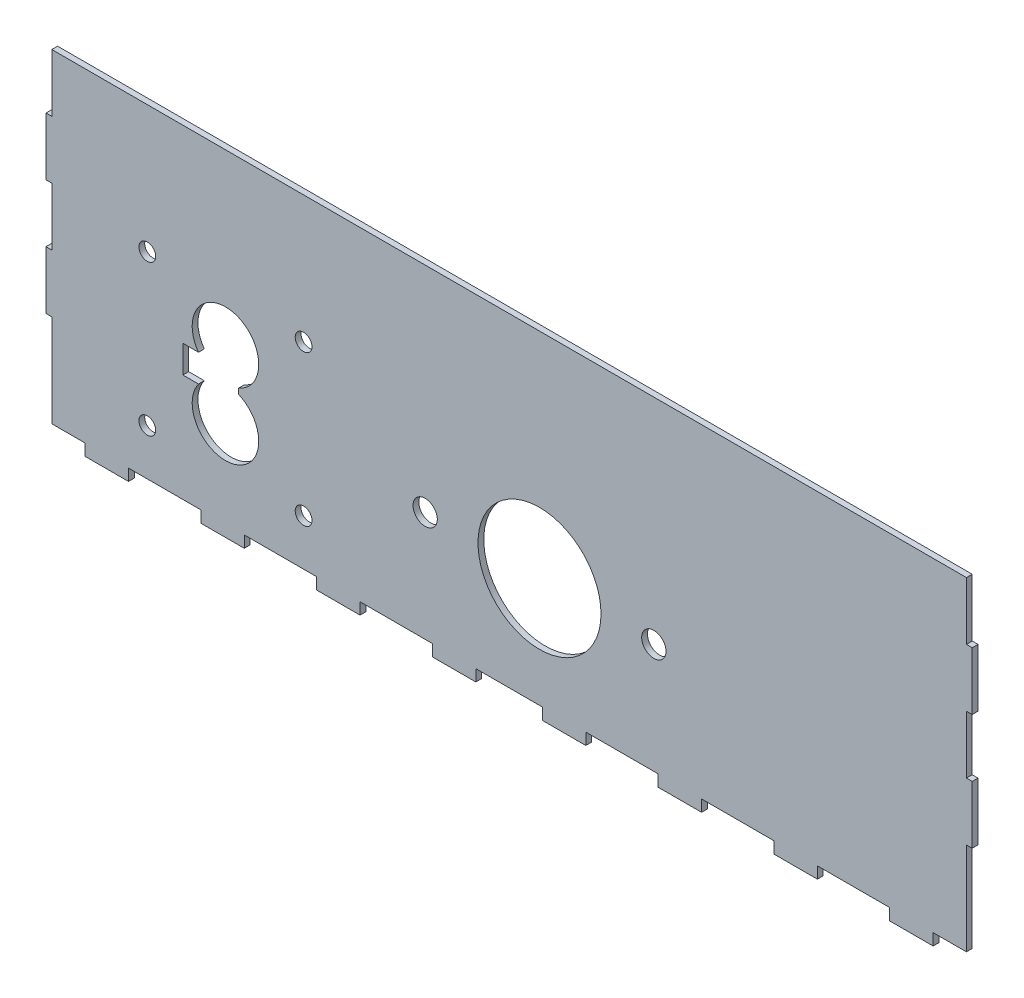
SolidWorks part; units mm, degrees
ref_plane "Front Plane" through (0, 0, 0) normal (0, 0, 1) x (1, 0, 0)
ref_plane "Top Plane" through (0, 0, 0) normal (0, 1, 0) x (1, 0, 0)
ref_plane "Right Plane" through (0, 0, 0) normal (1, 0, 0) x (0, 0, -1)
sketch "Sketch1" plane through (0, 0, 0) normal (0, 0, 1) x (1, 0, 0)
  line L0 (-93.5, -14.917) -> (-93.5, -13.083)
  line L1 (-158, -56) -> (-146.5, -56)
  line L2 (-158, -56) -> (-158, -24)
  line L3 (-158, 56) -> (-146.5, 56)
  line L4 (158, -56) -> (158, -24)
  line L5 (-158, -56) -> (158, 56) construction
  line L6 (-158, 56) -> (158, -56) construction
  line L7 (-131, -46) -> (-65, -46) construction
  line L8 (-131, -46) -> (-131, 18) construction
  line L9 (-131, 18) -> (-65, 18) construction
  line L10 (-65, -46) -> (-65, 18) construction
  line L11 (-131, -46) -> (-65, 18) construction
  line L12 (-131, 18) -> (-65, -46) construction
  line L13 (-112.7, -18.75) -> (-107.3106, -18.75)
  line L14 (-112.7, -18.75) -> (-112.7, -9.25)
  line L15 (-112.7, -9.25) -> (-107.3106, -9.25)
  line L17 (-112.7, -18.75) -> (-93.5, -9.25) construction
  line L18 (-112.7, -9.25) -> (-93.5, -18.75) construction
  line L19 (-106.5, -56) -> (-106.5, -60)
  line L21 (-146.5, -56) -> (-146.5, -60)
  line L22 (-146.5, -60) -> (-131.5, -60)
  line L23 (-131.5, -56) -> (-131.5, -60)
  line L25 (-91.5, -56) -> (-91.5, -60)
  line L26 (-106.5, -60) -> (-91.5, -60)
  line L27 (-66.5, -56) -> (-66.5, -60)
  line L29 (-51.5, -56) -> (-51.5, -60)
  line L30 (-66.5, -60) -> (-51.5, -60)
  line L31 (-26.5, -56) -> (-26.5, -60)
  line L33 (-11.5, -56) -> (-11.5, -60)
  line L34 (-26.5, -60) -> (-11.5, -60)
  line L35 (0, -55) -> (0, 55) construction
  line L37 (11.5, -56) -> (11.5, -60)
  line L38 (26.5, -60) -> (11.5, -60)
  line L39 (26.5, -56) -> (26.5, -60)
  line L41 (51.5, -56) -> (51.5, -60)
  line L42 (66.5, -60) -> (51.5, -60)
  line L43 (66.5, -56) -> (66.5, -60)
  line L45 (91.5, -56) -> (91.5, -60)
  line L46 (106.5, -60) -> (91.5, -60)
  line L47 (106.5, -56) -> (106.5, -60)
  line L48 (146.5, -60) -> (131.5, -60)
  line L49 (131.5, -56) -> (131.5, -60)
  line L51 (146.5, -56) -> (146.5, -60)
  line L52 (-131.5, -56) -> (-106.5, -56)
  line L53 (-91.5, -56) -> (-66.5, -56)
  line L54 (-51.5, -56) -> (-26.5, -56)
  line L55 (-11.5, -56) -> (11.5, -56)
  line L56 (26.5, -56) -> (51.5, -56)
  line L57 (66.5, -56) -> (91.5, -56)
  line L58 (106.5, -56) -> (131.5, -56)
  line L59 (146.5, -56) -> (158, -56)
  line L61 (-158, 36) -> (-160, 36)
  line L63 (-158, 16) -> (-160, 16)
  line L64 (-160, 36) -> (-160, 16)
  line L65 (-158, -4) -> (-160, -4)
  line L66 (-160, -4) -> (-160, -24)
  line L67 (-158, -24) -> (-160, -24)
  line L68 (158, -4) -> (160, -4)
  line L69 (160, -4) -> (160, -24)
  line L70 (158, -24) -> (160, -24)
  line L72 (158, 16) -> (160, 16)
  line L73 (160, 36) -> (160, 16)
  line L74 (158, 36) -> (160, 36)
  line L76 (-158, 36) -> (-158, 56)
  line L77 (-158, -4) -> (-158, 16)
  line L78 (158, 36) -> (158, 56)
  line L79 (158, -4) -> (158, 16)
  line L80 (-106.5, 56) -> (-106.5, 58)
  line L82 (-146.5, 56) -> (-146.5, 58)
  line L83 (-146.5, 58) -> (-131.5, 58)
  line L84 (-131.5, 56) -> (-131.5, 58)
  line L86 (-91.5, 56) -> (-91.5, 58)
  line L87 (-106.5, 58) -> (-91.5, 58)
  line L88 (-66.5, 56) -> (-66.5, 58)
  line L90 (-51.5, 56) -> (-51.5, 58)
  line L91 (-66.5, 58) -> (-51.5, 58)
  line L92 (-26.5, 56) -> (-26.5, 58)
  line L94 (-11.5, 56) -> (-11.5, 58)
  line L95 (-26.5, 58) -> (-11.5, 58)
  line L97 (11.5, 56) -> (11.5, 58)
  line L98 (26.5, 58) -> (11.5, 58)
  line L99 (26.5, 56) -> (26.5, 58)
  line L101 (51.5, 56) -> (51.5, 58)
  line L102 (66.5, 58) -> (51.5, 58)
  line L103 (66.5, 56) -> (66.5, 58)
  line L105 (91.5, 56) -> (91.5, 58)
  line L106 (106.5, 58) -> (91.5, 58)
  line L107 (106.5, 56) -> (106.5, 58)
  line L108 (146.5, 58) -> (131.5, 58)
  line L109 (131.5, 56) -> (131.5, 58)
  line L111 (146.5, 56) -> (146.5, 58)
  line L112 (-51.5, 56) -> (-26.5, 56)
  line L114 (-91.5, 56) -> (-66.5, 56)
  line L116 (-131.5, 56) -> (-106.5, 56)
  line L117 (-11.5, 56) -> (11.5, 56)
  line L118 (26.5, 56) -> (51.5, 56)
  line L119 (66.5, 56) -> (91.5, 56)
  line L120 (106.5, 56) -> (131.5, 56)
  line L121 (146.5, 56) -> (158, 56)
  circle A0 centre (10.5, -18) radius 21.25
  circle A1 centre (-29, -18) radius 4.2
  circle A2 centre (50, -18) radius 4.2
  circle A3 centre (-125, -40) radius 2.9
  circle A4 centre (-71, -40) radius 2.9
  arc A5 (-93.5, -13.083) -> (-107.3106, -9.25) centre (-98, -2.5) ccw
  arc A6 (-107.3106, -18.75) -> (-93.5, -14.917) centre (-98, -25.5) ccw
  circle A7 centre (-125, 12) radius 2.9
  circle A8 centre (-71, 12) radius 2.9
  point P0 (0, 0)
  point P13 (-98, -14)
  point P23 (-103.1, -14)
  dimension "D3" = 8.4
  dimension "D4" = 8.4
  dimension "D5" = 42.5
  dimension "D6" = 39.5
  dimension "D7" = 39.5
  dimension "D16" = 5.8
  dimension "D17" = 5.8
  dimension "D23" = 23
  dimension "D25" = 23
  dimension "D1" = 316
  dimension "D2" = 112
  dimension "D8" = 108
  dimension "D9" = 38
  dimension "D10" = 38
  dimension "D11" = 38
  dimension "D12" = 66
  dimension "D13" = 64
  dimension "D14" = 10
  dimension "D15" = 60
  dimension "D18" = 6
  dimension "D19" = 6
  dimension "D20" = 6
  dimension "D21" = 6
  dimension "D22" = 20.5
  dimension "D24" = 33
  dimension "D27" = 20.5
  dimension "D28" = 9.5
  dimension "D29" = 4.75
  dimension "D30" = 11.5
  dimension "D31" = 14.7
  dimension "D32" = 4.5
  dimension "D33" = 19.2
  dimension "D34" = 9.5
  dimension "D35" = 9.5
  dimension "D36" = 19.2
  dimension "D37" = 6
  dimension "D38" = 11.5
  dimension "D39" = 4
  dimension "D40" = 15
  dimension "D42" = 25
  dimension "D43" = 2
  dimension "D44" = 20
  dimension "D45" = 20
  dimension "D47" = 20
  dimension "D48" = 2
  dimension "D49" = 15
  dimension "D50" = 11.5
  dimension "D51" = 4
  dimension "D52" = 25
  dimension "D41" = 4
  dimension "D46" = 2
extrude "Boss-Extrude1" add sketch "Sketch1" along normal blind 2
sketch "Sketch2" plane through (0, 0, 2) normal (0, 0, 1) x (1, 0, 0)
  line L1 (-146.5, 58) -> (-131.5, 58)
  line L2 (-146.5, 58) -> (-146.5, 56)
  line L3 (-146.5, 56) -> (-131.5, 56)
  line L4 (-131.5, 58) -> (-131.5, 56)
  line L5 (-106.5, 58) -> (-91.5, 58)
  line L6 (-106.5, 58) -> (-106.5, 56)
  line L7 (-106.5, 56) -> (-91.5, 56)
  line L8 (-91.5, 58) -> (-91.5, 56)
  line L9 (-66.5, 58) -> (-51.5, 58)
  line L10 (-66.5, 58) -> (-66.5, 56)
  line L11 (-66.5, 56) -> (-51.5, 56)
  line L12 (-51.5, 58) -> (-51.5, 56)
  line L13 (-26.5, 58) -> (-11.5, 58)
  line L14 (-26.5, 58) -> (-26.5, 56)
  line L15 (-26.5, 56) -> (-11.5, 56)
  line L16 (-11.5, 58) -> (-11.5, 56)
  line L17 (11.5, 58) -> (26.5, 58)
  line L18 (11.5, 58) -> (11.5, 56)
  line L19 (11.5, 56) -> (26.5, 56)
  line L20 (26.5, 58) -> (26.5, 56)
  line L21 (51.5, 58) -> (66.5, 58)
  line L22 (51.5, 58) -> (51.5, 56)
  line L23 (51.5, 56) -> (66.5, 56)
  line L24 (66.5, 58) -> (66.5, 56)
  line L25 (91.5, 58) -> (106.5, 58)
  line L26 (91.5, 58) -> (91.5, 56)
  line L27 (91.5, 56) -> (106.5, 56)
  line L28 (106.5, 58) -> (106.5, 56)
  line L29 (131.5, 58) -> (146.5, 58)
  line L30 (131.5, 58) -> (131.5, 56)
  line L31 (131.5, 56) -> (146.5, 56)
  line L32 (146.5, 58) -> (146.5, 56)
extrude "Cut-Extrude1" cut sketch "Sketch2" against normal through all both and the other way through all
